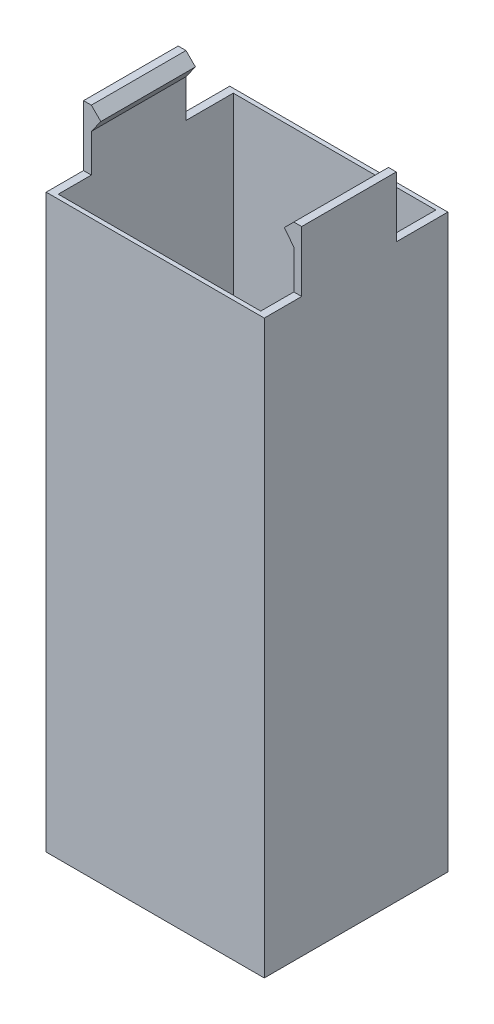
SolidWorks part; units mm, degrees
ref_plane "Front Plane" through (0, 0, 0) normal (0, 0, 1) x (1, 0, 0)
ref_plane "Top Plane" through (0, 0, 0) normal (0, 1, 0) x (1, 0, 0)
ref_plane "Right Plane" through (0, 0, 0) normal (1, 0, 0) x (0, 0, -1)
sketch "Sketch1" plane through (0, 0, 0) normal (0, 1, 0) x (1, 0, 0)
  line L0 (-23.05, 19.4) -> (42.3707, 19.4) construction
  line L1 (-23.05, 19.4) -> (23.05, 19.4)
  line L2 (-23.05, 19.4) -> (-23.05, -19.4)
  line L3 (-23.05, -19.4) -> (23.05, -19.4)
  line L4 (23.05, 19.4) -> (23.05, -19.4)
  line L5 (-23.05, 19.4) -> (23.05, -19.4) construction
  line L6 (-23.05, -19.4) -> (23.05, 19.4) construction
  line L7 (21.4, 18.5) -> (-21.4, 18.5)
  line L8 (21.4, 18.5) -> (21.4, -18.5)
  line L9 (21.4, -18.5) -> (-21.4, -18.5)
  line L10 (-21.4, 18.5) -> (-21.4, -18.5)
  line L11 (21.4, 18.5) -> (-21.4, -18.5) construction
  line L12 (21.4, -18.5) -> (-21.4, 18.5) construction
  point P0 (0, 0)
  point P6 (0, 0)
  dimension "D1" = 42.8
  dimension "D2" = 37
  dimension "D3" = 1.65
  dimension "D5" = 0.9
extrude "Boss-Extrude1" add sketch "Sketch1" along normal blind 120
sketch "Sketch2" plane through (0, 120, 0) normal (0, 1, 0) x (1, 0, 0)
  line L0 (-23.425, -1.5) -> (23.575, -1.5) construction
  line L1 (-23.05, 19.4) -> (-23.05, -19.4) construction
  line L3 (-21.4, 24.7662) -> (-21.4, -22.0296) construction
  line L4 (0, 23.9453) -> (0, -27.2839) construction
  line L5 (21.4, 8.5) -> (23.05, 8.5)
  line L6 (-21.4, -11.5) -> (-23.05, -11.5)
  line L7 (-21.4, -11.5) -> (-21.4, 8.5)
  line L8 (-21.4, 8.5) -> (-23.05, 8.5)
  line L9 (-23.05, -11.5) -> (-23.05, 8.5)
  line L10 (-21.4, -11.5) -> (-23.05, 8.5) construction
  line L11 (-21.4, 8.5) -> (-23.05, -11.5) construction
  line L12 (23.05, -11.5) -> (23.05, 8.5)
  line L13 (21.4, -11.5) -> (23.05, -11.5)
  line L14 (21.4, -11.5) -> (21.4, 8.5)
  line L15 (-21.4, 18.5) -> (-21.4, -18.5) construction
  point P11 (-22.225, -1.5)
  dimension "D2" = 20
  dimension "D3" = 20
extrude "Boss-Extrude2" add sketch "Sketch2" along normal blind 12.8
sketch "Sketch5" plane through (0, 0, 11.5) normal (0, 0, 1) x (1, 0, 0)
  line L0 (-19.4, 130.8) -> (19.4, 130.8) construction
  line L1 (21.4, 132.8) -> (21.4, 120) construction
  line L4 (-19.4, 130.8) -> (-21.4, 128)
  line L5 (-21.4, 128) -> (-21.4, 132.8)
  line L7 (-21.4, 132.8) -> (-19.4, 130.8)
  line L8 (21.4, 128.2) -> (21.4, 132.8)
  line L9 (19.4, 130.8) -> (21.4, 128.2)
  line L10 (21.4, 132.8) -> (19.4, 130.8)
  line L11 (-21.4, 132.8) -> (-21.4, 120) construction
  dimension "D1" = 10.8
  dimension "D2" = 2.8
  dimension "D3" = 2
  dimension "D4" = 2.6
  dimension "D5" = 2
extrude "Boss-Extrude5" add sketch "Sketch5" against normal up to surface (20 mm away) up to face at (22.225, 126.4, -8.5)
sketch "Sketch6" plane through (0, 0, 0) normal (0, -1, 0) x (1, 0, 0)
  line L0 (-23.05, 19.4) -> (23.05, 19.4) construction
  line L1 (23.05, 19.4) -> (-23.05, 19.4)
  line L2 (23.05, 19.4) -> (23.05, -19.4)
  line L3 (23.05, -19.4) -> (-23.05, -19.4)
  line L4 (-23.05, 19.4) -> (-23.05, -19.4)
extrude "Boss-Extrude6" add sketch "Sketch6" along normal blind 0.8
